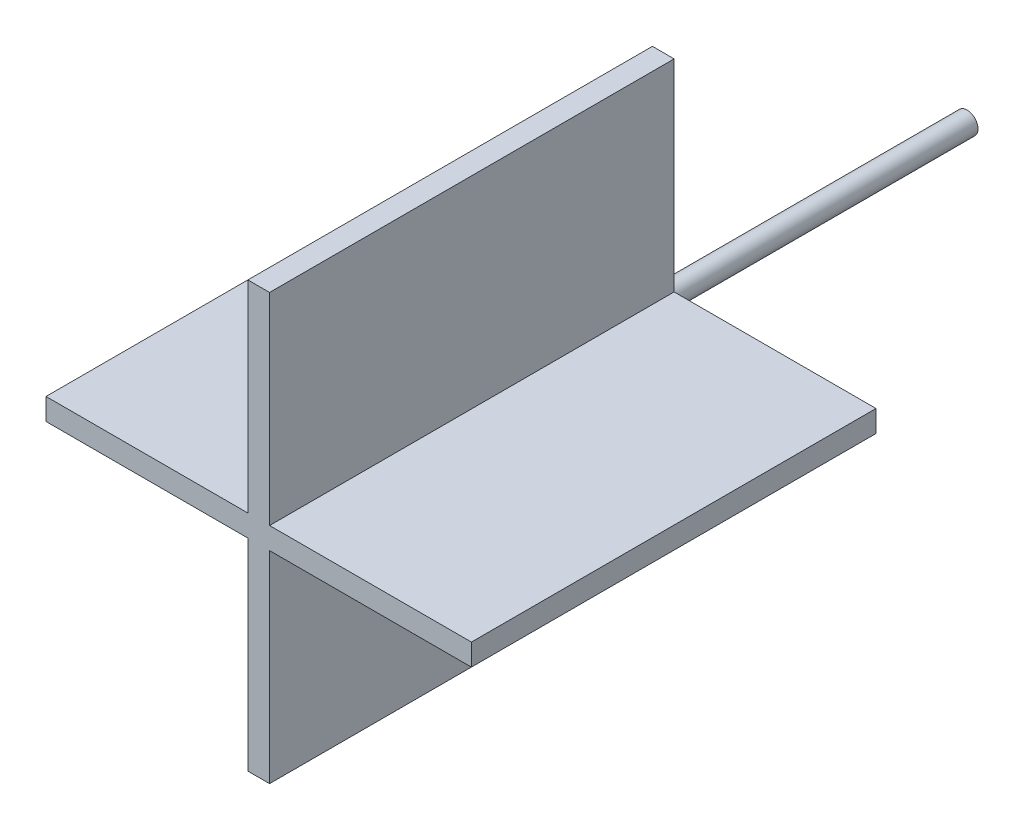
SolidWorks part; units mm, degrees
ref_plane "Přední rovina" through (0, 0, 0) normal (0, 0, 1) x (1, 0, 0)
ref_plane "Horní rovina" through (0, 0, 0) normal (0, 1, 0) x (1, 0, 0)
ref_plane "Pravá rovina" through (0, 0, 0) normal (1, 0, 0) x (0, 0, -1)
sketch "Skica1" plane through (0, 0, 0) normal (0, 0, 1) x (1, 0, 0)
  line L0 (0, 0) -> (-46.5, 0)
  line L1 (-46.5, 0) -> (-46.5, 5)
  line L2 (-46.5, 5) -> (0, 5)
  line L3 (0, 5) -> (0, 51.5)
  line L4 (0, 51.5) -> (5, 51.5)
  line L5 (5, 51.5) -> (5, 5)
  line L6 (5, 5) -> (51.5, 5)
  line L7 (51.5, 5) -> (51.5, 0)
  line L8 (51.5, 0) -> (5, 0)
  line L9 (5, 0) -> (5, -46.5)
  line L10 (5, -46.5) -> (0, -46.5)
  line L11 (0, -46.5) -> (0, 0)
  dimension "D1" = 5
  dimension "D2" = 5
  dimension "D3" = 5
  dimension "D4" = 5
  dimension "D5" = 46.5
  dimension "D6" = 46.5
  dimension "D7" = 46.5
  dimension "D8" = 46.5
extrude "Přidat vysunutím1" add sketch "Skica1" along normal blind 93.2
sketch "Skica2" plane through (0, 0, 0) normal (0, 0, 1) x (1, 0, 0)
  line L0 (5, -46.5) -> (5, 0) construction
  circle A1 centre (2.5, 2.537) radius 2.5
  point P3 (64.5718, 64.0718)
  point P6 (-57.4282, 3.3034)
  point P7 (2.5, 2.537)
  dimension "D1" = 5
  dimension "D2" = 2.5
extrude "Přidat vysunutím2" add sketch "Skica2" against normal blind 70
